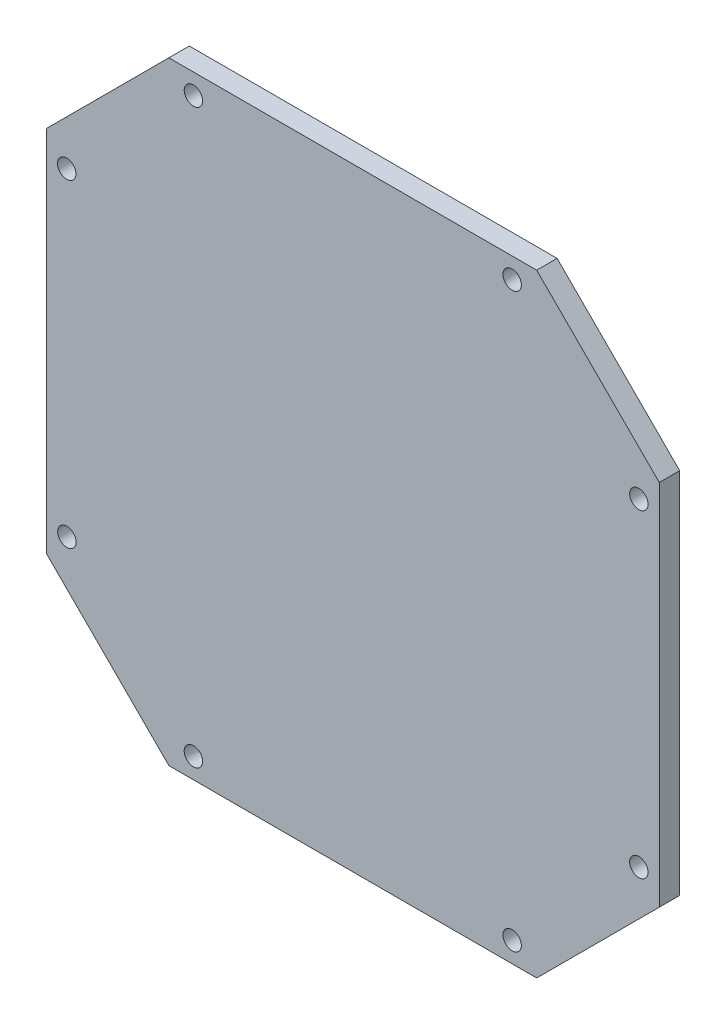
SolidWorks part; units mm, degrees
material "PETG"
ref_plane "Front Plane" through (0, 0, 0) normal (0, 0, 1) x (1, 0, 0)
ref_plane "Top Plane" through (0, 0, 0) normal (0, 1, 0) x (1, 0, 0)
ref_plane "Right Plane" through (0, 0, 0) normal (1, 0, 0) x (0, 0, -1)
sketch "Sketch1" plane through (0, 0, 0) normal (0, 0, 1) x (1, 0, 0)
  line L0 (0, 0) -> (0, 180)
  line L1 (0, 180) -> (60, 240)
  line L2 (60, 240) -> (240, 240)
  line L3 (240, 240) -> (300, 180)
  line L4 (300, 180) -> (300, 0)
  line L5 (300, 0) -> (240, -60)
  line L6 (240, -60) -> (60, -60)
  line L7 (60, -60) -> (0, 0)
  line L8 (-49.5651, 168) -> (377.8864, 168) construction
  line L9 (-73.2823, 12) -> (382.1315, 12) construction
  line L10 (228, 269.7939) -> (228, -83.8308) construction
  line L11 (72, 269.7939) -> (72, -122.5565) construction
  line L12 (10, 233.1809) -> (10, -50.791) construction
  line L13 (290, 226.4815) -> (290, -60) construction
  line L14 (-20.6111, -50) -> (362.8984, -50) construction
  line L15 (-55.6415, 230) -> (332.5287, 230) construction
  dimension "D1" = 45
  dimension "D2" = 135
  dimension "D3" = 135
  dimension "D4" = 60
  dimension "D5" = 300
  dimension "D6" = 300
  dimension "D7" = 10
  dimension "D8" = 62
  dimension "D9" = 218
  dimension "D10" = 280
  dimension "D11" = 10
  dimension "D12" = 62
  dimension "D13" = 156
  dimension "D14" = 218
extrude "Boss-Extrude1" add sketch "Sketch1" along normal blind 10
hole_wizard "Ø1.0mm Dowel Hole1" positions "Sketch2" profile "Sketch3" hole size "Ø1.0" standard "ISO"
sketch "Sketch2" plane through (0, 0, 0) normal (0, 0, -1) x (-1, 0, 0)
  line L0 (-72, 269.7939) -> (-72, -122.5565) construction
  line L1 (55.6415, 230) -> (-332.5287, 230) construction
  line L2 (-228, 269.7939) -> (-228, -83.8308) construction
  line L3 (49.5651, 168) -> (-377.8864, 168) construction
  line L4 (-290, 226.4815) -> (-290, -60) construction
  line L5 (73.2823, 12) -> (-382.1315, 12) construction
  line L6 (20.6111, -50) -> (-362.8984, -50) construction
  line L7 (-10, 233.1809) -> (-10, -50.791) construction
  point P0 (-72, 230)
  point P6 (-228, 230)
  point P10 (-290, 168)
  point P16 (-290, 12)
  point P20 (-228, -50)
  point P24 (-72, -50)
  point P26 (-10.0957, 12)
  point P28 (-10, 168)
sketch "Sketch3" plane through (72, 230, 0) normal (1, 0, 0) x (0, 1, 0)
  line L0 (0, 0) -> (0, 32)
  line L1 (0, 32) -> (4.5, 29.2961)
  line L2 (4.5, 29.2961) -> (4.5, 0)
  line L5 (4.5, 0) -> (0, 0)
  line L10 (0, 32) -> (-4.5, 29.2961) construction
  line L11 (0, -6.35) -> (0, 107.95) construction
  dimension "Hole Dia." = 9
  dimension "Hole Depth" = 32
  dimension "Drill Angle" = 118
